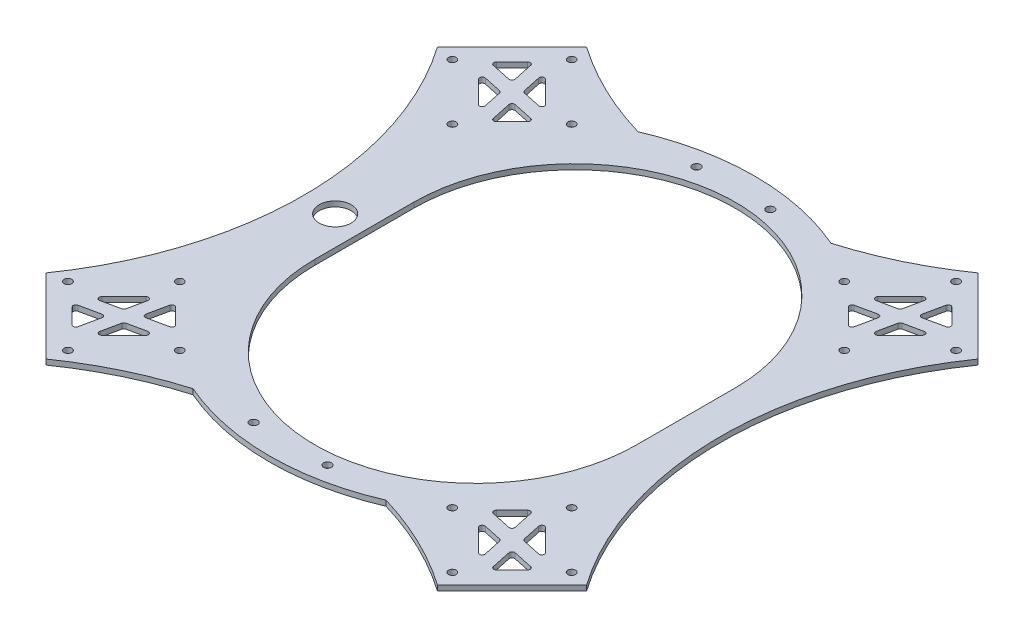
SolidWorks part; units mm, degrees
material "Thornel Mat VMA"
ref_plane "前视基准面" through (0, 0, 0) normal (0, 0, 1) x (1, 0, 0)
ref_plane "上视基准面" through (0, 0, 0) normal (0, 1, 0) x (1, 0, 0)
ref_plane "右视基准面" through (0, 0, 0) normal (1, 0, 0) x (0, 0, -1)
sketch "草图1" plane through (0, 0, 0) normal (0, 1, 0) x (1, 0, 0)
  line L0 (-74.2462, 102.5305) -> (-102.5305, 74.2462)
  line L1 (74.2462, 102.5305) -> (-74.2462, 102.5305)
  line L2 (102.5305, 74.2462) -> (102.5305, -74.2462)
  line L3 (74.2462, -102.5305) -> (-74.2462, -102.5305)
  line L4 (-102.5305, 74.2462) -> (-102.5305, -74.2462)
  line L5 (102.5305, 102.5305) -> (-102.5305, -102.5305) construction
  line L6 (102.5305, -102.5305) -> (-102.5305, 102.5305) construction
  line L7 (102.5305, -74.2462) -> (74.2462, -102.5305)
  line L8 (-102.5305, -74.2462) -> (-74.2462, -102.5305)
  line L9 (74.2462, 102.5305) -> (102.5305, 74.2462)
  line L10 (-102.5305, 102.5305) -> (-102.5305, -102.5305) construction
  line L11 (-102.5305, -102.5305) -> (102.5305, -102.5305) construction
  line L12 (102.5305, -102.5305) -> (102.5305, 102.5305) construction
  line L13 (102.5305, 102.5305) -> (-102.5305, 102.5305) construction
  point P0 (0, 0)
  dimension "D1" = 250
  dimension "D2" = 40
extrude "凸台-拉伸1" add sketch "草图1" along normal blind 2
hole_wizard "孔1" positions "草图4" profile "草图5" legacy
sketch "草图4" plane through (0, 2, 0) normal (0, 1, 0) x (1, 0, 0)
  point P0 (-95.5397, 72.9159)
  point P3 (-74.3265, 51.7027)
  point P6 (-51.6991, 74.3301)
  point P9 (-72.9123, 95.5433)
  point P16 (72.9159, 95.5397)
  point P17 (51.7027, 74.3265)
  point P18 (74.3301, 51.6991)
  point P19 (95.5433, 72.9123)
  point P20 (95.5397, -72.9159)
  point P21 (74.3265, -51.7027)
  point P22 (51.6991, -74.3301)
  point P23 (72.9123, -95.5433)
  point P24 (-72.9159, -95.5397)
  point P25 (-51.7027, -74.3265)
  point P26 (-74.3301, -51.6991)
  point P27 (-95.5433, -72.9123)
  dimension "D1" = 4
sketch "草图5" plane through (-95.5397, 2, -72.9159) normal (1, 0, 0) x (0, 0, 1)
  line L0 (0, 0) -> (0, 100)
  line L1 (0, 100) -> (1.45, 100)
  line L2 (1.45, 100) -> (1.45, 0)
  line L3 (1.45, 0) -> (0, 0)
  line L4 (0, 110) -> (0, -10) construction
  dimension "直径" = 2.9
  dimension "深度" = 100
sketch "草图7" plane through (0, 2, 0) normal (0, 1, 0) x (1, 0, 0)
  line L0 (-95.5397, 72.9159) -> (-51.6991, 74.3301) construction
  line L1 (-86.393, 80.4842) -> (-80.4806, 86.3966)
  line L2 (-84.1601, 71.4358) -> (-75.8066, 63.0823)
  line L3 (-71.4322, 84.1637) -> (-63.0787, 75.8102)
  line L4 (-66.7582, 60.8494) -> (-60.8458, 66.7618)
  line L5 (-89.8008, 77.0764) -> (-57.438, 70.1696) construction
  line L6 (-77.0728, 89.8044) -> (-70.166, 57.4416) construction
  line L7 (-49.2242, 67.6126) -> (-79.6109, 97.9993) construction
  line L8 (-74.2462, 102.5305) -> (-102.5305, 74.2462) construction
  line L9 (-85.8946, 78.7991) -> (-78.378, 77.1949)
  line L10 (-83.2443, 73.1208) -> (-76.36, 71.6516)
  line L11 (-87.6941, 79.1831) -> (-89.8008, 77.0764) construction
  line L12 (-89.8008, 77.0764) -> (-86.5509, 73.8265) construction
  line L13 (-60.6879, 73.4195) -> (-57.438, 70.1696) construction
  line L14 (-57.438, 70.1696) -> (-59.5447, 68.0629) construction
  line L15 (-67.4604, 74.8648) -> (-68.504, 69.975) construction
  line L16 (-73.6194, 73.623) -> (-67.2554, 79.987) construction
  line L17 (-74.1216, 63.9981) -> (-75.5908, 70.8824)
  line L18 (-68.4433, 61.3478) -> (-70.0475, 68.8644)
  line L19 (-70.8788, 75.5944) -> (-63.9945, 74.1252)
  line L20 (-77.1913, 78.3816) -> (-78.7955, 85.8982)
  line L21 (-68.8608, 70.0511) -> (-61.3442, 68.4469)
  line L22 (-71.648, 76.3636) -> (-73.1172, 83.2479)
  line L23 (80.4842, 86.393) -> (86.3966, 80.4806)
  line L24 (71.4358, 84.1601) -> (63.0823, 75.8066)
  line L25 (84.1637, 71.4322) -> (75.8102, 63.0787)
  line L26 (60.8494, 66.7582) -> (66.7618, 60.8458)
  line L27 (78.7991, 85.8946) -> (77.1949, 78.378)
  line L28 (73.1208, 83.2443) -> (71.6516, 76.36)
  line L29 (63.9981, 74.1216) -> (70.8824, 75.5908)
  line L30 (61.3478, 68.4433) -> (68.8644, 70.0475)
  line L31 (75.5944, 70.8788) -> (74.1252, 63.9945)
  line L32 (78.3816, 77.1913) -> (85.8982, 78.7955)
  line L33 (70.0511, 68.8608) -> (68.4469, 61.3442)
  line L34 (76.3636, 71.648) -> (83.2479, 73.1172)
  line L35 (72.9159, 95.5397) -> (74.3301, 51.6991) construction
  line L36 (77.0764, 89.8008) -> (70.1696, 57.438) construction
  line L37 (89.8044, 77.0728) -> (57.4416, 70.166) construction
  line L38 (79.1831, 87.6941) -> (77.0764, 89.8008) construction
  line L39 (77.0764, 89.8008) -> (73.8265, 86.5509) construction
  line L40 (73.4195, 60.6879) -> (70.1696, 57.438) construction
  line L41 (70.1696, 57.438) -> (68.0629, 59.5447) construction
  line L42 (74.8648, 67.4604) -> (69.975, 68.504) construction
  line L43 (73.623, 73.6194) -> (79.987, 67.2554) construction
  line L44 (86.393, -80.4842) -> (80.4806, -86.3966)
  line L45 (84.1601, -71.4358) -> (75.8066, -63.0823)
  line L46 (71.4322, -84.1637) -> (63.0787, -75.8102)
  line L47 (66.7582, -60.8494) -> (60.8458, -66.7618)
  line L48 (85.8946, -78.7991) -> (78.378, -77.1949)
  line L49 (83.2443, -73.1208) -> (76.36, -71.6516)
  line L50 (74.1216, -63.9981) -> (75.5908, -70.8824)
  line L51 (68.4433, -61.3478) -> (70.0475, -68.8644)
  line L52 (70.8788, -75.5944) -> (63.9945, -74.1252)
  line L53 (77.1913, -78.3816) -> (78.7955, -85.8982)
  line L54 (68.8608, -70.0511) -> (61.3442, -68.4469)
  line L55 (71.648, -76.3636) -> (73.1172, -83.2479)
  line L56 (95.5397, -72.9159) -> (51.6991, -74.3301) construction
  line L57 (89.8008, -77.0764) -> (57.438, -70.1696) construction
  line L58 (77.0728, -89.8044) -> (70.166, -57.4416) construction
  line L59 (87.6941, -79.1831) -> (89.8008, -77.0764) construction
  line L60 (89.8008, -77.0764) -> (86.5509, -73.8265) construction
  line L61 (60.6879, -73.4195) -> (57.438, -70.1696) construction
  line L62 (57.438, -70.1696) -> (59.5447, -68.0629) construction
  line L63 (67.4604, -74.8648) -> (68.504, -69.975) construction
  line L64 (73.6194, -73.623) -> (67.2554, -79.987) construction
  line L65 (-80.4842, -86.393) -> (-86.3966, -80.4806)
  line L66 (-71.4358, -84.1601) -> (-63.0823, -75.8066)
  line L67 (-84.1637, -71.4322) -> (-75.8102, -63.0787)
  line L68 (-60.8494, -66.7582) -> (-66.7618, -60.8458)
  line L69 (-78.7991, -85.8946) -> (-77.1949, -78.378)
  line L70 (-73.1208, -83.2443) -> (-71.6516, -76.36)
  line L71 (-63.9981, -74.1216) -> (-70.8824, -75.5908)
  line L72 (-61.3478, -68.4433) -> (-68.8644, -70.0475)
  line L73 (-75.5944, -70.8788) -> (-74.1252, -63.9945)
  line L74 (-78.3816, -77.1913) -> (-85.8982, -78.7955)
  line L75 (-70.0511, -68.8608) -> (-68.4469, -61.3442)
  line L76 (-76.3636, -71.648) -> (-83.2479, -73.1172)
  line L77 (-72.9159, -95.5397) -> (-74.3301, -51.6991) construction
  line L78 (-77.0764, -89.8008) -> (-70.1696, -57.438) construction
  line L79 (-89.8044, -77.0728) -> (-57.4416, -70.166) construction
  line L80 (-79.1831, -87.6941) -> (-77.0764, -89.8008) construction
  line L81 (-77.0764, -89.8008) -> (-73.8265, -86.5509) construction
  line L82 (-73.4195, -60.6879) -> (-70.1696, -57.438) construction
  line L83 (-70.1696, -57.438) -> (-68.0629, -59.5447) construction
  line L84 (-74.8648, -67.4604) -> (-69.975, -68.504) construction
  line L85 (-73.623, -73.6194) -> (-79.987, -67.2554) construction
  arc A0 (-63.0787, 75.8102) -> (-63.9945, 74.1252) centre (-63.7858, 75.1031) cw
  arc A1 (-70.8788, 75.5944) -> (-71.648, 76.3636) centre (-70.67, 76.5724) cw
  arc A2 (-71.4322, 84.1637) -> (-73.1172, 83.2479) centre (-72.1393, 83.4566) ccw
  arc A3 (-78.7955, 85.8982) -> (-80.4806, 86.3966) centre (-79.7735, 85.6895) ccw
  arc A4 (-85.8946, 78.7991) -> (-86.393, 80.4842) centre (-85.6859, 79.7771) cw
  arc A5 (-78.378, 77.1949) -> (-77.1913, 78.3816) centre (-78.1693, 78.1729) ccw
  arc A6 (-66.7582, 60.8494) -> (-68.4433, 61.3478) centre (-67.4653, 61.5565) cw
  arc A7 (-60.8458, 66.7618) -> (-61.3442, 68.4469) centre (-61.5529, 67.4689) ccw
  arc A8 (-68.8608, 70.0511) -> (-70.0475, 68.8644) centre (-69.0695, 69.0731) ccw
  arc A9 (-75.8066, 63.0823) -> (-74.1216, 63.9981) centre (-75.0995, 63.7894) ccw
  arc A10 (-75.5908, 70.8824) -> (-76.36, 71.6516) centre (-76.5688, 70.6736) ccw
  arc A11 (-83.2443, 73.1208) -> (-84.1601, 71.4358) centre (-83.453, 72.1429) ccw
  arc A12 (75.8102, 63.0787) -> (74.1252, 63.9945) centre (75.1031, 63.7858) cw
  arc A13 (75.5944, 70.8788) -> (76.3636, 71.648) centre (76.5724, 70.67) cw
  arc A14 (84.1637, 71.4322) -> (83.2479, 73.1172) centre (83.4566, 72.1393) ccw
  arc A15 (85.8982, 78.7955) -> (86.3966, 80.4806) centre (85.6895, 79.7735) ccw
  arc A16 (78.7991, 85.8946) -> (80.4842, 86.393) centre (79.7771, 85.6859) cw
  arc A17 (77.1949, 78.378) -> (78.3816, 77.1913) centre (78.1729, 78.1693) ccw
  arc A18 (60.8494, 66.7582) -> (61.3478, 68.4433) centre (61.5565, 67.4653) cw
  arc A19 (66.7618, 60.8458) -> (68.4469, 61.3442) centre (67.4689, 61.5529) ccw
  arc A20 (70.0511, 68.8608) -> (68.8644, 70.0475) centre (69.0731, 69.0695) ccw
  arc A21 (63.0823, 75.8066) -> (63.9981, 74.1216) centre (63.7894, 75.0995) ccw
  arc A22 (70.8824, 75.5908) -> (71.6516, 76.36) centre (70.6736, 76.5688) ccw
  arc A23 (73.1208, 83.2443) -> (71.4358, 84.1601) centre (72.1429, 83.453) ccw
  arc A24 (63.0787, -75.8102) -> (63.9945, -74.1252) centre (63.7858, -75.1031) cw
  arc A25 (70.8788, -75.5944) -> (71.648, -76.3636) centre (70.67, -76.5724) cw
  arc A26 (71.4322, -84.1637) -> (73.1172, -83.2479) centre (72.1393, -83.4566) ccw
  arc A27 (78.7955, -85.8982) -> (80.4806, -86.3966) centre (79.7735, -85.6895) ccw
  arc A28 (85.8946, -78.7991) -> (86.393, -80.4842) centre (85.6859, -79.7771) cw
  arc A29 (78.378, -77.1949) -> (77.1913, -78.3816) centre (78.1693, -78.1729) ccw
  arc A30 (66.7582, -60.8494) -> (68.4433, -61.3478) centre (67.4653, -61.5565) cw
  arc A31 (60.8458, -66.7618) -> (61.3442, -68.4469) centre (61.5529, -67.4689) ccw
  arc A32 (68.8608, -70.0511) -> (70.0475, -68.8644) centre (69.0695, -69.0731) ccw
  arc A33 (75.8066, -63.0823) -> (74.1216, -63.9981) centre (75.0995, -63.7894) ccw
  arc A34 (75.5908, -70.8824) -> (76.36, -71.6516) centre (76.5688, -70.6736) ccw
  arc A35 (83.2443, -73.1208) -> (84.1601, -71.4358) centre (83.453, -72.1429) ccw
  arc A36 (-75.8102, -63.0787) -> (-74.1252, -63.9945) centre (-75.1031, -63.7858) cw
  arc A37 (-75.5944, -70.8788) -> (-76.3636, -71.648) centre (-76.5724, -70.67) cw
  arc A38 (-84.1637, -71.4322) -> (-83.2479, -73.1172) centre (-83.4566, -72.1393) ccw
  arc A39 (-85.8982, -78.7955) -> (-86.3966, -80.4806) centre (-85.6895, -79.7735) ccw
  arc A40 (-78.7991, -85.8946) -> (-80.4842, -86.393) centre (-79.7771, -85.6859) cw
  arc A41 (-77.1949, -78.378) -> (-78.3816, -77.1913) centre (-78.1729, -78.1693) ccw
  arc A42 (-60.8494, -66.7582) -> (-61.3478, -68.4433) centre (-61.5565, -67.4653) cw
  arc A43 (-66.7618, -60.8458) -> (-68.4469, -61.3442) centre (-67.4689, -61.5529) ccw
  arc A44 (-70.0511, -68.8608) -> (-68.8644, -70.0475) centre (-69.0731, -69.0695) ccw
  arc A45 (-63.0823, -75.8066) -> (-63.9981, -74.1216) centre (-63.7894, -75.0995) ccw
  arc A46 (-70.8824, -75.5908) -> (-71.6516, -76.36) centre (-70.6736, -76.5688) ccw
  arc A47 (-73.1208, -83.2443) -> (-71.4358, -84.1601) centre (-72.1429, -83.453) ccw
  point P5 (-73.6194, 73.623)
  point P14 (-72.9123, 95.5433)
  point P21 (-67.9822, 72.4199)
  point P38 (-71.5127, 75.7297)
  point P41 (-73.8229, 86.5545)
  point P44 (-79.1795, 87.6977)
  point P50 (-76.8693, 76.8729)
  point P53 (-68.0593, 59.5483)
  point P59 (-70.3695, 70.3731)
  point P62 (-73.4159, 60.6915)
  point P73 (73.623, 73.6194)
  point P84 (72.4199, 67.9822)
  point P126 (73.6194, -73.623)
  point P137 (67.9822, -72.4199)
  point P179 (-73.623, -73.6194)
  point P190 (-72.4199, -67.9822)
  point P230 (0, 0)
  dimension "D4" = 1
  dimension "D1" = 7
  dimension "D2" = 7
  dimension "D3" = 5
  dimension "D5" = 4
extrude "切除-拉伸2" cut sketch "草图7" against normal through all both and the other way through all
sketch "草图8" plane through (0, 2, 0) normal (0, 1, 0) x (1, 0, 0)
  line L0 (-208.5651, 0) -> (0, 0) construction
  line L1 (-102.5305, -74.2462) -> (-50.5427, 0) construction
  line L3 (0, 0) -> (-88.3883, -88.3883) construction
  line L4 (-102.5305, -74.2462) -> (-74.2462, -102.5305) construction
  line L5 (0, 102.5305) -> (0, -102.5305) construction
  line L6 (74.2462, 102.5305) -> (-74.2462, 102.5305) construction
  line L7 (-74.2462, -102.5305) -> (74.2462, -102.5305) construction
  circle A0 centre (-208.5651, 0) radius 129.4443
  circle A2 centre (0, 208.5651) radius 129.4443
  circle A3 centre (208.5651, 0) radius 129.4443
  circle A4 centre (0, -208.5651) radius 129.4443
  point P28 (0, 0)
  dimension "D1" = 10
  dimension "D2" = 4
extrude "切除-拉伸3" cut sketch "草图8" against normal through all both and the other way through all
sketch "草图9" plane through (0, 2, 0) normal (0, 1, 0) x (1, 0, 0)
  line L0 (0, 0) -> (-79.1207, 0) construction
  arc A0 (-102.5305, -74.2462) -> (-102.5305, 74.2462) centre (-208.5651, 0) ccw construction
  circle A1 centre (-67.0707, 0) radius 6.05
  point P8 (-73.1207, 0)
  dimension "D1" = 12.1
  dimension "D2" = 6
extrude "切除-拉伸4" cut sketch "草图9" against normal through all both and the other way through all
sketch "草图11" plane through (0, 2, 0) normal (0, 1, 0) x (1, 0, 0)
  line L0 (5.9793, 0) -> (0, 0) construction
  line L1 (-61.0207, 0) -> (-54.0207, 0) construction
  circle A0 centre (5.9793, 0) radius 60
  circle A1 centre (-67.0707, 0) radius 6.05 construction
  point P3 (-54.0207, 0)
  point P7 (-61.0207, 0)
  dimension "D1" = 120
  dimension "D2" = 7
extrude "切除-拉伸6" cut sketch "草图11" against normal through all both and the other way through all
sketch "草图15" plane through (0, 2, 0) normal (0, 1, 0) x (1, 0, 0)
  line L1 (-40.3412, 82.6837) -> (-31.9185, 62.6852)
  line L2 (44.6358, 80.4465) -> (36.2732, 60.2701)
  line L3 (-42.4295, -81.6317) -> (-34.5316, -61.2845)
  line L4 (41.391, -82.1632) -> (34.5498, -61.2743)
  arc A0 (-42.4295, -81.6317) -> (-5.8723, -91.8124) centre (0, 0) ccw
  arc A1 (-5.8723, 91.8124) -> (-40.3412, 82.6837) centre (0, 0) ccw
  arc A2 (-34.5316, -61.2845) -> (34.5498, -61.2743) centre (0, 0) ccw
  arc A3 (36.2732, 60.2701) -> (-31.9185, 62.6852) centre (0, 0) ccw
  arc A4 (44.6358, 80.4465) -> (-5.8723, 91.8124) centre (0, 0) ccw
  arc A7 (-5.8723, -91.8124) -> (41.391, -82.1632) centre (0, 0) ccw
  point P1 (0, 0)
  point P4 (0, 0)
  point P20 (-4, 91.913)
  dimension "D1" = 92
extrude "凸台-拉伸3" add sketch "草图15" against normal up to surface (2 mm away) up to face at (5.9793, 0, 60)
hole_wizard "孔2" positions "草图16" profile "草图17" legacy
sketch "草图16" plane through (0, 2, 0) normal (0, 1, 0) x (1, 0, 0)
  line L0 (-14, 154) -> (14, 154) construction
  line L3 (-14, -154) -> (14, -154) construction
  line L5 (0, -154) -> (0, 154) construction
  line L7 (10, 154) -> (-10, 154) construction
  line L8 (10, -154) -> (-10, -154) construction
  line L9 (-14, -84) -> (14, -84) construction
  line L10 (0, -84) -> (0, 224) construction
  line L11 (-14, 84) -> (14, 84) construction
  point P0 (-14, 154)
  point P3 (14, 154)
  point P12 (-14, -154)
  point P15 (14, -154)
  point P54 (-14, -84)
  point P55 (14, -84)
  point P64 (-14, 84)
  point P65 (14, 84)
  dimension "D1" = 28
  dimension "D2" = 28
  dimension "D5" = 168
  dimension "D3" = 2
  dimension "D4" = 2
sketch "草图17" plane through (-14, 2, -154) normal (1, 0, 0) x (0, 0, 1)
  line L0 (0, 0) -> (0, 100)
  line L1 (0, 100) -> (1.5, 100)
  line L2 (1.5, 100) -> (1.5, 0)
  line L3 (1.5, 0) -> (0, 0)
  line L4 (0, 110) -> (0, -10) construction
  dimension "直径" = 3
  dimension "深度" = 100
sketch "草图18" plane through (0, 2, 0) normal (0, 1, 0) x (1, 0, 0)
  line L0 (-56.0207, 0) -> (4.9793, 0) construction
  line L1 (4.9793, 18.75) -> (4.9793, -18.75) construction
  line L2 (65.9793, 18.75) -> (65.9793, -18.75)
  line L3 (-56.0207, 18.75) -> (-56.0207, -18.75)
  arc A1 (65.9793, 18.75) -> (-56.0207, 18.75) centre (4.9793, 18.75) ccw
  arc A2 (-56.0207, -18.75) -> (65.9793, -18.75) centre (4.9793, -18.75) ccw
  circle A3 centre (5.9793, 0) radius 60 construction
  point P0 (-56.0207, 0)
  point P1 (-54.0207, 0)
  point P5 (5.9793, 0)
  point P8 (4.9793, 0)
  dimension "D1" = 61
  dimension "D2" = 2
  dimension "D3" = 37.5
extrude "切除-拉伸7" cut sketch "草图18" against normal through all both and the other way through all
